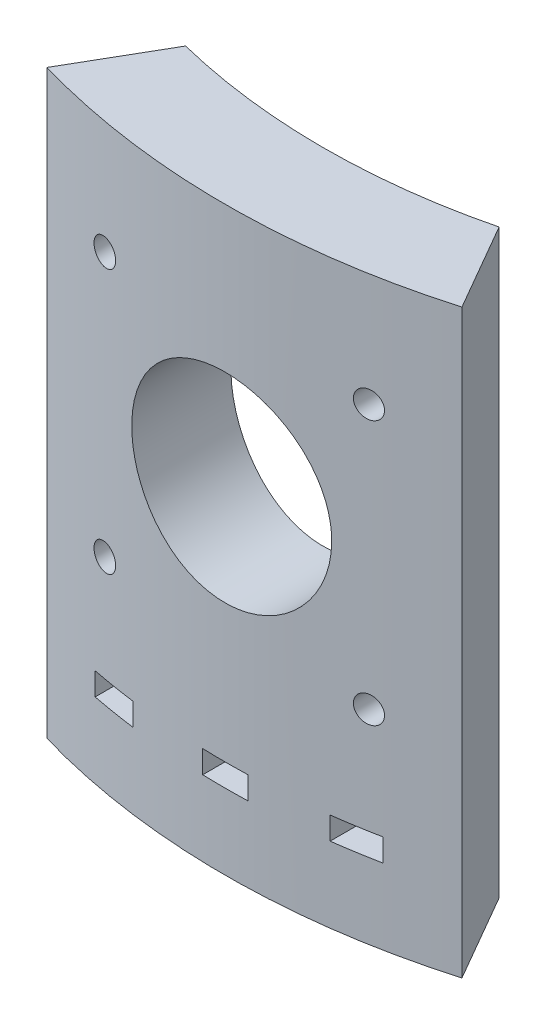
SolidWorks part; units mm, degrees
ref_plane "Спереди" through (0, 0, 0) normal (0, 0, 1) x (1, 0, 0)
ref_plane "Сверху" through (0, 0, 0) normal (0, 1, 0) x (1, 0, 0)
ref_plane "Справа" through (0, 0, 0) normal (1, 0, 0) x (0, 0, -1)
sketch "Эскиз1" plane through (0, 0, 0) normal (0, 1, 0) x (-1, 0, 0)
  line L0 (27.5, 9.1039) -> (20.7736, -2.5467)
  line L1 (-27.5, 9.1039) -> (-20.7736, -2.5467)
  line L2 (0, 13) -> (0, 0) construction
  line L3 (0, -86) -> (0, 0) construction
  arc A0 (-27.5, 9.1039) -> (27.5, 9.1039) centre (0, -86) cw
  arc A2 (-20.7736, -2.5467) -> (20.7736, -2.5467) centre (0, -86) cw
  dimension "D3" = 86
  dimension "D4" = 99
  dimension "D1" = 55
  dimension "D2" = 30
  dimension "D5" = 30
  dimension "D6" = 13
extrude "Бобышка-Вытянуть1" add sketch "Эскиз1" along normal blind 77
sketch "Эскиз2" plane through (0, 0, 0) normal (0, -1, 0) x (1, 0, 0)
  line L0 (0, -86) -> (0, 6.5) construction
  line L1 (0, 13) -> (0, 0) construction
  line L2 (-27.5, 9.1039) -> (-20.7736, -2.5467) construction
  line L3 (27.5, 9.1039) -> (20.7736, -2.5467) construction
  line L4 (-16.0596, 5.0788) -> (0, -86) construction
  line L5 (0, -86) -> (16.0596, 5.0788) construction
  arc A0 (-24.1368, 3.2786) -> (24.1368, 3.2786) centre (0, -86) cw construction
  circle A1 centre (0, 6.5) radius 1.75
  circle A2 centre (16.0596, 5.0788) radius 1.75
  circle A3 centre (-16.0596, 5.0788) radius 1.75
  dimension "D3" = 3.5
  dimension "D4" = 3.5
  dimension "D5" = 3.5
  dimension "D1" = 10
  dimension "D2" = 10
extrude "Вырез-Вытянуть1" cut sketch "Эскиз2" against normal blind 20
ref_plane "Плоскость1" through (0, 0, 13) normal (0, 0, 1) x (1, 0, 0)
sketch "Эскиз3" plane through (0, 0, 13) normal (0, 0, 1) x (1, 0, 0)
  line L0 (-16.0596, 0) -> (-16.0596, 11.5) construction
  line L1 (-16.0596, 11.5) -> (16.0596, 11.5) construction
  line L2 (16.0596, 11.5) -> (16.0596, 0) construction
  line L3 (0, 0) -> (0, 11.5) construction
  line L4 (27.5, 0) -> (-27.5, 0) construction
  line L5 (-17.8096, 0) -> (-14.3096, 0) construction
  line L6 (-19.0596, 13) -> (-13.0596, 13)
  line L7 (-19.0596, 13) -> (-19.0596, 10)
  line L8 (-19.0596, 10) -> (-13.0596, 10)
  line L9 (-13.0596, 13) -> (-13.0596, 10)
  line L10 (-19.0596, 13) -> (-13.0596, 10) construction
  line L11 (-19.0596, 10) -> (-13.0596, 13) construction
  line L12 (-3, 13) -> (3, 13)
  line L13 (-3, 13) -> (-3, 10)
  line L14 (-3, 10) -> (3, 10)
  line L15 (3, 13) -> (3, 10)
  line L16 (-3, 13) -> (3, 10) construction
  line L17 (-3, 10) -> (3, 13) construction
  line L18 (13.0596, 13) -> (19.0596, 13)
  line L19 (13.0596, 13) -> (13.0596, 10)
  line L20 (13.0596, 10) -> (19.0596, 10)
  line L21 (19.0596, 13) -> (19.0596, 10)
  line L22 (13.0596, 13) -> (19.0596, 10) construction
  line L23 (13.0596, 10) -> (19.0596, 13) construction
  line L24 (14.3096, 0) -> (17.8096, 0) construction
  dimension "D1" = 11.5
  dimension "D2" = 6
  dimension "D3" = 6
  dimension "D4" = 6
  dimension "D5" = 3
  dimension "D6" = 3
  dimension "D7" = 3
extrude "Вырез-Вытянуть2" cut sketch "Эскиз3" against normal through all
sketch "Эскиз4" plane through (0, 0, 13) normal (0, 0, 1) x (1, 0, 0)
  line L0 (0, 44.5) -> (0, 0) construction
  circle A0 centre (0, 44.5) radius 13.25
  dimension "D1" = 26.5
  dimension "D2" = 44.5
extrude "Вырез-Вытянуть3" cut sketch "Эскиз4" against normal through all
sketch "Эскиз5" plane through (0, 77, 0) normal (0, 1, 0) x (1, 0, 0)
  line L0 (16.6948, -11.5822) -> (0, 41.3669) construction
  line L1 (0, 41.3669) -> (0, 0) construction
  line L2 (0, 41.3669) -> (-16.6948, -11.5822) construction
  arc A0 (-27.5, -9.1039) -> (27.5, -9.1039) centre (0, 86) ccw construction
  arc A1 (-20.7736, 2.5467) -> (20.7736, 2.5467) centre (0, 86) ccw construction
  dimension "D1" = 35
  dimension "D2" = 17.5
ref_plane "Плоскость4" through (0, 0, 13) normal (0, 0, 1) x (1, 0, 0)
sketch "Эскиз7" plane through (0, 0, 13) normal (0, 0, 1) x (1, 0, 0)
  line L1 (-17.5, 62) -> (17.5, 62) construction
  line L2 (-17.5, 62) -> (-17.5, 27) construction
  line L3 (-17.5, 27) -> (17.5, 27) construction
  line L4 (17.5, 62) -> (17.5, 27) construction
  line L5 (-17.5, 62) -> (17.5, 27) construction
  line L6 (-17.5, 27) -> (17.5, 62) construction
  circle A0 centre (-17.5, 62) radius 1.75
  circle A1 centre (17.5, 62) radius 1.75
  circle A2 centre (17.5, 27) radius 1.75
  circle A3 centre (-17.5, 27) radius 1.75
  point P0 (0, 44.5)
  dimension "D3" = 3.5
  dimension "D4" = 3.5
  dimension "D5" = 3.5
  dimension "D6" = 3.5
  dimension "D1" = 35
  dimension "D2" = 35
extrude "Вырез-Вытянуть4" cut sketch "Эскиз7" against normal through all
sketch "Эскиз8" plane through (0, 0, 13) normal (0, 0, 1) x (1, 0, 0)
  line L0 (0, 57.75) -> (0, 31.25)
  line L1 (0, 31.25) -> (-13.25, 44.5)
  line L2 (-13.25, 44.5) -> (13.25, 44.5)
  circle A0 centre (0, 44.5) radius 13.25 construction
  point P8 (0, 44.5)
